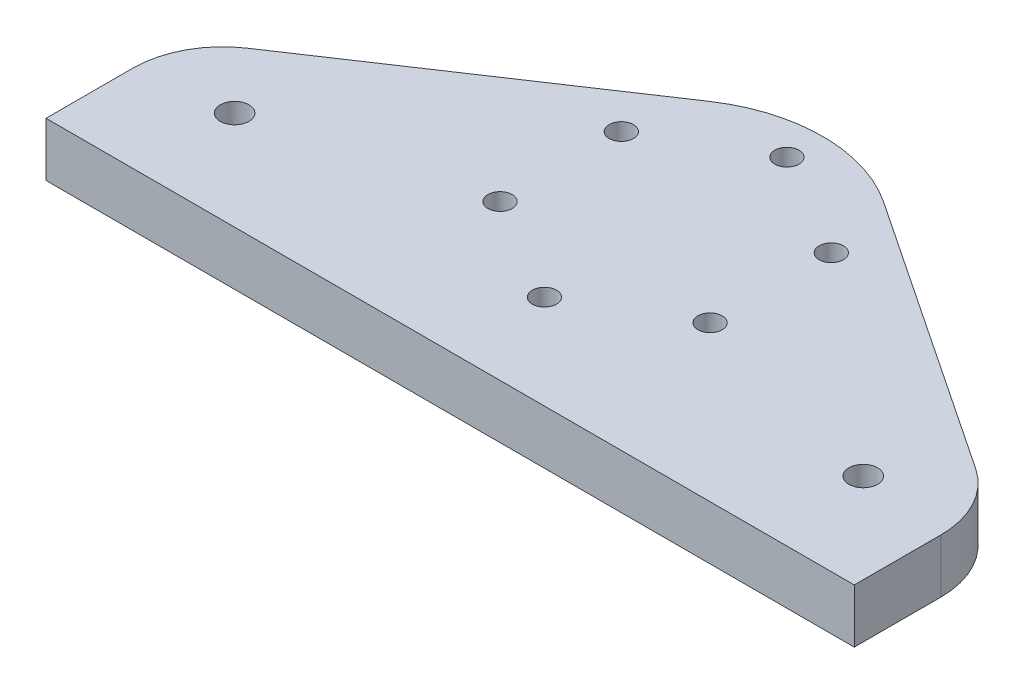
SolidWorks part; units mm, degrees
material "Thornel Mat VMA"
ref_plane "前视基准面" through (0, 0, 0) normal (0, 0, 1) x (1, 0, 0)
ref_plane "上视基准面" through (0, 0, 0) normal (0, 1, 0) x (1, 0, 0)
ref_plane "右视基准面" through (0, 0, 0) normal (1, 0, 0) x (0, 0, -1)
other "Configuration Table"
sketch "草图1" plane through (0, 0, 0) normal (0, 1, 0) x (1, 0, 0)
  line L3 (-9.7165, 14.5547) -> (-45, -9)
  line L4 (-45, -9) -> (-45, -24)
  line L5 (-45, -24) -> (45, -24)
  line L6 (45, -24) -> (45, -9)
  line L7 (45, -9) -> (9.7165, 14.5547)
  line L8 (0, 0) -> (0, 40.4038) construction
  arc A0 (9.7165, 14.5547) -> (-9.7165, 14.5547) centre (0, 0) ccw
  dimension "D1" = 17.5
  dimension "D2" = 90
  dimension "D3" = 24
  dimension "D4" = 15
extrude "凸台-拉伸1" add sketch "草图1" along normal blind 6
sketch "草图2" plane through (0, 6, 0) normal (0, 1, 0) x (1, 0, 0)
  line L5 (-9.7165, 14.5547) -> (-45, -9)
  line L6 (-45, -9) -> (-45, -24)
  line L7 (-45, -24) -> (45, -24)
  line L8 (45, -24) -> (45, -9)
  line L9 (45, -9) -> (9.7165, 14.5547)
  line L10 (-9.7165, 14.5547) -> (-45, -9) construction
  line L11 (-45, -9) -> (-45, -24) construction
  line L12 (-45, -24) -> (45, -24) construction
  line L13 (45, -24) -> (45, -9) construction
  line L14 (45, -9) -> (9.7165, 14.5547) construction
  circle A0 centre (0, 13.5) radius 1.35
  arc A1 (9.7165, 14.5547) -> (-9.7165, 14.5547) centre (0, 0) ccw
  arc A2 (9.7165, 14.5547) -> (-9.7165, 14.5547) centre (0, 0) ccw construction
  circle A3 centre (11.6913, 6.75) radius 1.35
  circle A4 centre (11.6913, -6.75) radius 1.35
  circle A5 centre (0, -13.5) radius 1.35
  circle A6 centre (-11.6913, -6.75) radius 1.35
  circle A7 centre (-11.6913, 6.75) radius 1.35
  point P21 (0, 0)
  dimension "D2" = 2.7
  dimension "D4" = 13.5
  dimension "D1" = 0
  dimension "D3" = 6
extrude "切除-拉伸1" cut sketch "草图2" against normal up to surface (6 mm away) up to face at (0, 0, 5.6575)
fillet "圆角1" radius 10 2 edges at (45, 3, 9) (-45, 3, 9)
sketch "草图3" plane through (0, 0, 0) normal (0, -1, 0) x (1, 0, 0)
  line L0 (0, 0) -> (0, 29.7445) construction
  line L1 (-45, 14.3478) -> (-45, 24) construction
  line L2 (-45, 24) -> (45, 24) construction
  circle A0 centre (-35, 13) radius 1.6
  circle A1 centre (35, 13) radius 1.6
  dimension "D3" = 3.2
  dimension "D1" = 10
  dimension "D2" = 11
extrude "切除-拉伸2" cut sketch "草图3" against normal up to surface (6 mm away) up to face at (0, 6, -12.15)
